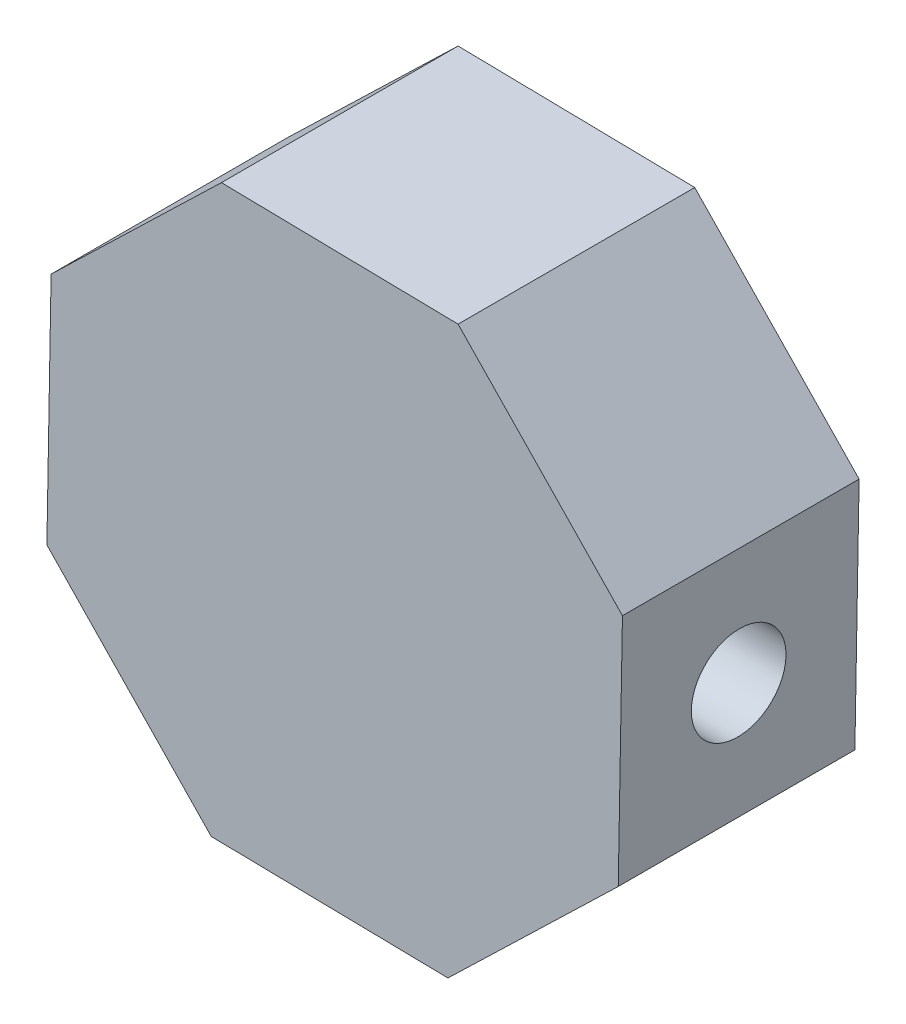
SolidWorks part; units mm, degrees
ref_plane "Front Plane" through (0, 0, 0) normal (0, 0, 1) x (1, 0, 0)
ref_plane "Top Plane" through (0, 0, 0) normal (0, 1, 0) x (1, 0, 0)
ref_plane "Right Plane" through (0, 0, 0) normal (1, 0, 0) x (0, 0, -1)
sketch "Sketch5" plane through (0, 0, 0) normal (0, 0, 1) x (1, 0, 0)
  line L7 (17.3164, -7.015) -> (17.5426, 5.685)
  line L8 (17.5426, 5.685) -> (8.7222, 14.8251)
  line L9 (8.7222, 14.8251) -> (-3.9778, 15.0513)
  line L10 (-3.9778, 15.0513) -> (-13.1179, 6.2309)
  line L11 (-13.1179, 6.2309) -> (-13.3441, -6.4691)
  line L12 (-13.3441, -6.4691) -> (-4.5237, -15.6092)
  line L13 (-4.5237, -15.6092) -> (8.1763, -15.8354)
  line L14 (8.1763, -15.8354) -> (17.3164, -7.015)
  circle A1 centre (2.0993, -0.3921) radius 15.3327 construction
  dimension "D1" = 12.7
extrude "Boss-Extrude2" add sketch "Sketch5" along normal blind 12.7
sketch "Sketch6" plane through (17.4358, -0.3105, 0) normal (0.9998, -0.0178, 0) x (0, 0, -1)
  line L0 (-12.7, -6.7056) -> (0, 5.9964)
  line L1 (0, 5.9964) -> (0, -6.7056)
  line L2 (0, -6.7056) -> (-12.7, 5.9964)
  circle A0 centre (-6.35, -0.3546) radius 2.54
extrude "Cut-Extrude3" cut sketch "Sketch6" against normal blind 12.7 contours L0 A0 L2 | L2 A0 L0 | L0 A0 L2 | L2 A0 L0
sketch "Sketch7" plane through (0, 0, 0) normal (0, 0, -1) x (-1, 0, 0)
  line L2 (13.1179, 6.2309) -> (13.3441, -6.4691) construction
  line L3 (13.2192, 0.5459) -> (13.3441, -6.4691)
  line L5 (-17.5426, 5.685) -> (-17.3164, -7.015)
  line L7 (13.1179, 6.2309) -> (4.5237, -15.6092)
  line L9 (-8.7222, 14.8251) -> (3.9778, 15.0513)
  circle A0 centre (-2.0993, -0.3921) radius 3.175
extrude "Cut-Extrude5" cut sketch "Sketch7" against normal blind 2.54 contours A0
equation "\"0..10inin\"=0.5"
